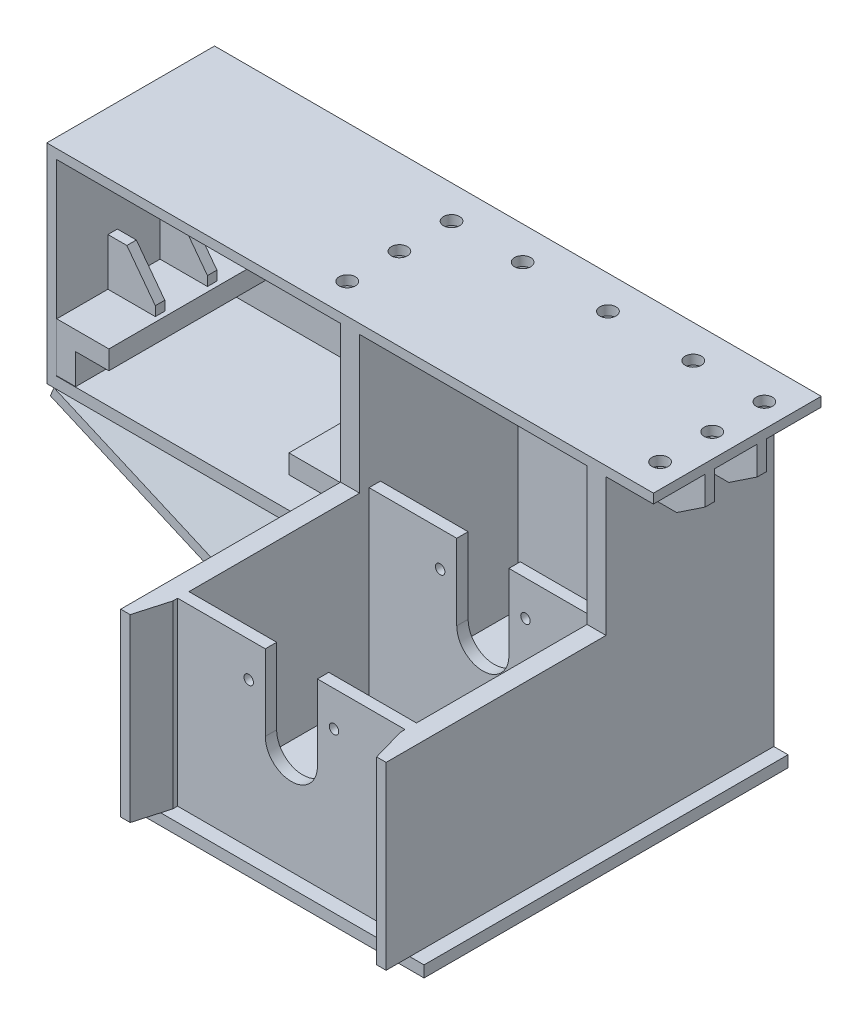
SolidWorks part; units mm, degrees
ref_plane "前视基准面" through (0, 0, 0) normal (0, 0, 1) x (1, 0, 0)
ref_plane "上视基准面" through (0, 0, 0) normal (0, 1, 0) x (1, 0, 0)
ref_plane "右视基准面" through (0, 0, 0) normal (1, 0, 0) x (0, 0, -1)
sketch "草图1" plane through (0, 0, 0) normal (0, 1, 0) x (1, 0, 0)
  line L0 (450, -858) -> (450, 49142) construction
  line L1 (0, 0) -> (640, 0)
  line L2 (0, 0) -> (0, 177)
  line L3 (0, 177) -> (640, 177)
  line L4 (640, 0) -> (640, 177)
  circle A0 centre (615, 142) radius 8.5
  circle A1 centre (615, 87) radius 8.5
  circle A2 centre (615, 32) radius 8.5
  circle A3 centre (540, 142) radius 8.5
  circle A4 centre (450, 142) radius 8.5
  circle A5 centre (360, 142) radius 8.5
  circle A6 centre (285, 142) radius 8.5
  circle A7 centre (285, 32) radius 8.5
  circle A8 centre (285, 87) radius 8.5
  dimension "D3" = 17
  dimension "D1" = 640
  dimension "D2" = 177
  dimension "D4" = 25
  dimension "D5" = 55
  dimension "D6" = 32
  dimension "D7" = 55
  dimension "D8" = 165
  dimension "D9" = 90
  dimension "D10" = 165
  dimension "D11" = 90
extrude "凸台-拉伸1" add sketch "草图1" along normal blind 10
sketch "草图2" plane through (0, 0, 0) normal (0, -1, 0) x (1, 0, 0)
  line L0 (450, -1145) -> (450, 48855) construction
  line L2 (640, -177) -> (0, -177) construction
  line L3 (590, -177) -> (570, -177)
  line L4 (590, -177) -> (590, 0)
  line L5 (590, 0) -> (570, 0)
  line L6 (570, -177) -> (570, 0)
  line L7 (0, 0) -> (640, 0) construction
  line L9 (330, -177) -> (310, -177)
  line L10 (330, -177) -> (330, 0)
  line L11 (330, 0) -> (310, 0)
  line L12 (310, -177) -> (310, 0)
  dimension "D1" = 20
  dimension "D2" = 20
  dimension "D3" = 120
  dimension "D4" = 120
extrude "凸台-拉伸2" add sketch "草图2" along normal blind 335
sketch "草图3" plane through (0, 0, 0) normal (0, 0, 1) x (1, 0, 0)
  line L0 (570, -335) -> (570, 0) construction
  line L1 (590, -335) -> (570, -335)
  line L2 (590, -335) -> (590, -145)
  line L3 (590, -145) -> (570, -145)
  line L4 (570, -335) -> (570, -145)
  line L5 (310, -335) -> (310, 0) construction
  line L6 (330, -335) -> (310, -335)
  line L7 (330, -335) -> (330, -145)
  line L8 (330, -145) -> (310, -145)
  line L9 (310, -335) -> (310, -145)
  dimension "D1" = 190
  dimension "D2" = 190
extrude "凸台-拉伸3" add sketch "草图3" along normal blind 232
sketch "草图4" plane through (0, -335, 0) normal (0, -1, 0) x (1, 0, 0)
  line L0 (330, 232) -> (320, 232)
  line L1 (310, 232) -> (330, 232) construction
  line L2 (320, 232) -> (330, 197)
  line L3 (330, -177) -> (330, 232) construction
  line L4 (330, 197) -> (330, 232)
  line L5 (570, 232) -> (580, 232)
  line L6 (570, 232) -> (590, 232) construction
  line L7 (580, 232) -> (570, 197)
  line L8 (570, 232) -> (570, -177) construction
  line L9 (570, 197) -> (570, 232)
  dimension "D1" = 35
  dimension "D2" = 10
  dimension "D3" = 10
  dimension "D4" = 35
extrude "切除-拉伸1" cut sketch "草图4" against normal through all
sketch "草图5" plane through (0, 0, 0) normal (0, -1, 0) x (-1, 0, 0)
  line L0 (-570, -197) -> (-570, 177) construction
  line L1 (-330, 177) -> (-570, 177)
  line L2 (-330, 177) -> (-330, 167)
  line L3 (-330, 167) -> (-570, 167)
  line L4 (-570, 177) -> (-570, 167)
  dimension "D1" = 10
extrude "凸台-拉伸4" add sketch "草图5" along normal blind 335
sketch "草图6" plane through (0, 0, -177) normal (0, 0, -1) x (-1, 0, 0)
  line L0 (-450, -1335) -> (-450, 48665) construction
  line L1 (-310, -335) -> (-590, -335) construction
  circle A0 centre (-450, -225) radius 35
  point P5 (-450, -335)
  dimension "D1" = 70
  dimension "D2" = 110
extrude "切除-拉伸2" cut sketch "草图6" against normal blind 10
sketch "草图7" plane through (310, 0, 0) normal (-1, 0, 0) x (0, 0, 1)
  line L0 (232, -335) -> (-177, -335) construction
  line L1 (-177, 0) -> (-167, 0)
  line L2 (-177, 0) -> (-177, -335)
  line L3 (-177, -335) -> (-167, -335)
  line L4 (-167, 0) -> (-167, -335)
  dimension "D1" = 10
extrude "凸台-拉伸5" add sketch "草图7" along normal blind 300
sketch "草图8" plane through (0, 0, -177) normal (0, 0, -1) x (-1, 0, 0)
  line L0 (-10, -211) -> (-295, -335)
  line L1 (-10, 0) -> (-10, -335) construction
  line L2 (-10, -335) -> (-590, -335) construction
  line L3 (-295, -335) -> (-10, -335)
  line L4 (-10, -335) -> (-10, -211)
  line L5 (-640, 10) -> (0, 10) construction
  circle A0 centre (-217, -76) radius 6
  circle A1 centre (-103, -76) radius 6
  circle A2 centre (-217, -119) radius 6
  circle A3 centre (-103, -119) radius 6
  dimension "D3" = 12
  dimension "D1" = 124
  dimension "D2" = 285
  dimension "D4" = 93
  dimension "D5" = 114
  dimension "D6" = 43
  dimension "D7" = 129
extrude "切除-拉伸3" cut sketch "草图8" against normal blind 10
sketch "草图9" plane through (10, 0, 0) normal (-1, 0, 0) x (0, 0, 1)
  line L1 (-177, 0) -> (0, 0)
  line L2 (-177, 0) -> (-177, -210)
  line L3 (-177, -210) -> (0, -210)
  line L4 (0, 0) -> (0, -210)
  dimension "D1" = 177
  dimension "D2" = 210
extrude "凸台-拉伸6" add sketch "草图9" along normal blind 10
sketch "草图11" plane through (0, 0, -177) normal (0, 0, -1) x (-1, 0, 0)
  line L0 (-7.7108, -210.004) -> (-295, -335)
  line L1 (-295, -335) -> (-291.0104, -344.1697)
  line L2 (-291.0104, -344.1697) -> (-3.712, -219.1697)
  line L3 (-3.712, -219.1697) -> (-7.6976, -210.0092)
  line L4 (-10, -211) -> (-295, -335) construction
  line L5 (0, -210) -> (-10, -210) construction
  line L6 (-7.6976, -210.0092) -> (-7.7108, -210.004)
  point P0 (-7.7016, -210)
  dimension "D2" = 10
extrude "凸台-拉伸7" add sketch "草图11" against normal blind 177 separate body
ref_plane "基准面1" through (0, 0, 180) normal (0, 0, 1) x (1, 0, 0)
sketch "草图12" plane through (0, 0, 180) normal (0, 0, 1) x (1, 0, 0)
  line L0 (330, -335) -> (570, -335)
  line L1 (570, -335) -> (570, -145)
  line L2 (330, -145) -> (422.5, -145)
  line L3 (330, -145) -> (330, -335)
  line L4 (450, -1335) -> (450, 48665) construction
  line L5 (-550, -225) -> (49450, -225) construction
  line L6 (422.5, -145) -> (422.5, -225)
  line L7 (570, -145) -> (477.5, -145)
  line L8 (477.5, -145) -> (477.5, -225)
  line L9 (-638.5489, -182) -> (49361.4511, -182) construction
  arc A0 (422.5, -225) -> (477.5, -225) centre (450, -225) ccw
  circle A1 centre (405, -182) radius 5
  circle A2 centre (495, -182) radius 5
  point P11 (450, -335)
  dimension "D1" = 27.5
  dimension "D3" = 10
  dimension "D2" = 43
  dimension "D4" = 45
  dimension "D5" = 45
extrude "凸台-拉伸8" add sketch "草图12" along normal blind 12
pattern_linear "阵列(线性)2" count 2 spacing 202 along (0, 0, -1) of "凸台-拉伸8"
sketch "草图14" plane through (0, 0, -167) normal (0, 0, 1) x (1, 0, 0)
  line L0 (310, -335) -> (310, 0) construction
  line L1 (10, -210) -> (310, -210)
  line L2 (10, -210) -> (10, -198)
  line L3 (10, -198) -> (310, -198)
  line L4 (310, -210) -> (310, -198)
  dimension "D1" = 12
extrude "凸台-拉伸9" add sketch "草图14" along normal blind 167
sketch "草图15" plane through (10, 0, 0) normal (1, 0, 0) x (0, 0, -1)
  line L0 (0, -198) -> (167, -198) construction
  line L1 (0.5, -166) -> (166.5, -166)
  line L2 (0.5, -166) -> (0.5, -198)
  line L3 (0.5, -198) -> (166.5, -198)
  line L4 (166.5, -166) -> (166.5, -198)
  line L5 (167, -198) -> (167, 0) construction
  line L6 (0, -198) -> (0, 0) construction
  dimension "D1" = 32
  dimension "D2" = 0.5
  dimension "D3" = 0.5
extrude "凸台-拉伸10" add sketch "草图15" along normal blind 20
sketch "草图16" plane through (0, 0, -0.5) normal (0, 0, 1) x (1, 0, 0)
  line L0 (310, -146) -> (310, -198)
  line L1 (10, -166) -> (65, -166)
  line L2 (10, -166) -> (10, -146)
  line L3 (10, -146) -> (65, -146)
  line L4 (65, -166) -> (65, -146)
  line L6 (310, -198) -> (290, -198)
  line L7 (310, -198) -> (10, -198) construction
  line L8 (290, -198) -> (290, -166)
  line L9 (290, -166) -> (255, -166)
  line L10 (255, -166) -> (255, -146)
  line L11 (255, -146) -> (310, -146)
  dimension "D1" = 55
  dimension "D2" = 20
  dimension "D3" = 20
extrude "凸台-拉伸11" add sketch "草图16" against normal blind 166
sketch "草图17" plane through (0, 0, -0.5) normal (0, 0, 1) x (1, 0, 0)
  line L0 (10, -146) -> (60, -146)
  line L2 (65, -146) -> (10, -146) construction
  line L3 (60, -146) -> (60, -136)
  line L6 (60, -136) -> (30, -96)
  line L7 (30, -96) -> (10, -96)
  line L9 (10, -96) -> (10, -146)
  line L10 (310, -146) -> (260, -146)
  line L11 (260, -146) -> (260, -136)
  line L12 (260, -136) -> (290, -96)
  line L13 (290, -96) -> (310, -96)
  line L15 (310, -96) -> (310, -146)
  dimension "D1" = 50
  dimension "D2" = 50
  dimension "D3" = 50
  dimension "D4" = 50
  dimension "D5" = 20
  dimension "D6" = 10
  dimension "D7" = 10
  dimension "D8" = 20
extrude "凸台-拉伸12" add sketch "草图17" against normal blind 166
sketch "草图18" plane through (0, -96, 0) normal (0, 1, 0) x (1, 0, 0)
  line L0 (285, 142) -> (285, 87) construction
  line L1 (285, 87) -> (285, 32) construction
  line L2 (-715, 114.5) -> (49285, 114.5) construction
  line L3 (-715, 59.5) -> (49285, 59.5) construction
  line L4 (-715, 87) -> (49285, 87) construction
  line L6 (10, 166.5) -> (310, 166.5)
  line L7 (10, 166.5) -> (10, 119.5)
  line L8 (10, 119.5) -> (310, 119.5)
  line L9 (310, 166.5) -> (310, 119.5)
  line L10 (10, 109.5) -> (310, 109.5)
  line L11 (10, 109.5) -> (10, 64.5)
  line L12 (10, 64.5) -> (310, 64.5)
  line L13 (310, 109.5) -> (310, 64.5)
  line L14 (10, 54.5) -> (310, 54.5)
  line L15 (10, 54.5) -> (10, 0.5)
  line L16 (10, 0.5) -> (310, 0.5)
  line L17 (310, 54.5) -> (310, 0.5)
  line L18 (10, 166.5) -> (10, 0.5) construction
  line L19 (310, 166.5) -> (310, 0.5) construction
  line L20 (310, 0.5) -> (290, 0.5) construction
  line L21 (310, 166.5) -> (290, 166.5) construction
  point P8 (285, 114.5)
  point P15 (285, 59.5)
  dimension "D1" = 10
  dimension "D2" = 10
extrude "切除-拉伸4" cut sketch "草图18" against normal blind 50
ref_plane "基准面2" through (590, 0, 0) normal (1, 0, 0) x (0, 0, -1)
sketch "草图20" plane through (0, 0, -54.5) normal (0, 0, 1) x (1, 0, 0)
  line L0 (590, 0) -> (640, 0)
  line L1 (640, 0) -> (640, -30)
  line L2 (640, -30) -> (610, -50)
  line L3 (610, -50) -> (590, -50)
  line L4 (590, -145) -> (590, 0) construction
  line L5 (590, -50) -> (590, 0)
  line L6 (310, 0) -> (276.6667, 0)
  line L7 (10, 0) -> (310, 0) construction
  line L8 (276.6667, 0) -> (276.6667, -30)
  line L9 (276.6667, -30) -> (290, -50)
  line L10 (290, -50) -> (310, -50)
  line L11 (310, -198) -> (310, 0) construction
  line L12 (310, -50) -> (310, 0)
  line L13 (10, 0) -> (10, -50)
  line L14 (10, -198) -> (10, 0) construction
  line L15 (10, -50) -> (30, -50)
  line L16 (30, -50) -> (60, -30)
  line L17 (60, -30) -> (60, 0)
  line L18 (60, 0) -> (10, 0)
  dimension "D1" = 20
  dimension "D2" = 30
  dimension "D3" = 30
  dimension "D4" = 30
  dimension "D5" = 50
  dimension "D6" = 50
extrude "凸台-拉伸13" add sketch "草图20" against normal blind 10
pattern_linear "阵列(线性)1" count 2 spacing 55 along (0, 0, -1) of "凸台-拉伸13"
sketch "草图21" plane through (0, -335, 0) normal (0, -1, 0) x (-1, 0, 0)
  line L1 (-291.0104, 177) -> (-605, 177)
  line L2 (-291.0104, 177) -> (-291.0104, -207)
  line L3 (-291.0104, -207) -> (-605, -207)
  line L4 (-605, 177) -> (-605, -207)
  line L6 (-291.0104, 0) -> (-291.0104, 177) construction
  line L7 (-295, 177) -> (-590, 177) construction
  line L8 (-295, 0) -> (-295, 177) construction
  dimension "D1" = 310
  dimension "D2" = 384
extrude "凸台-拉伸18" add sketch "草图21" along normal blind 12
